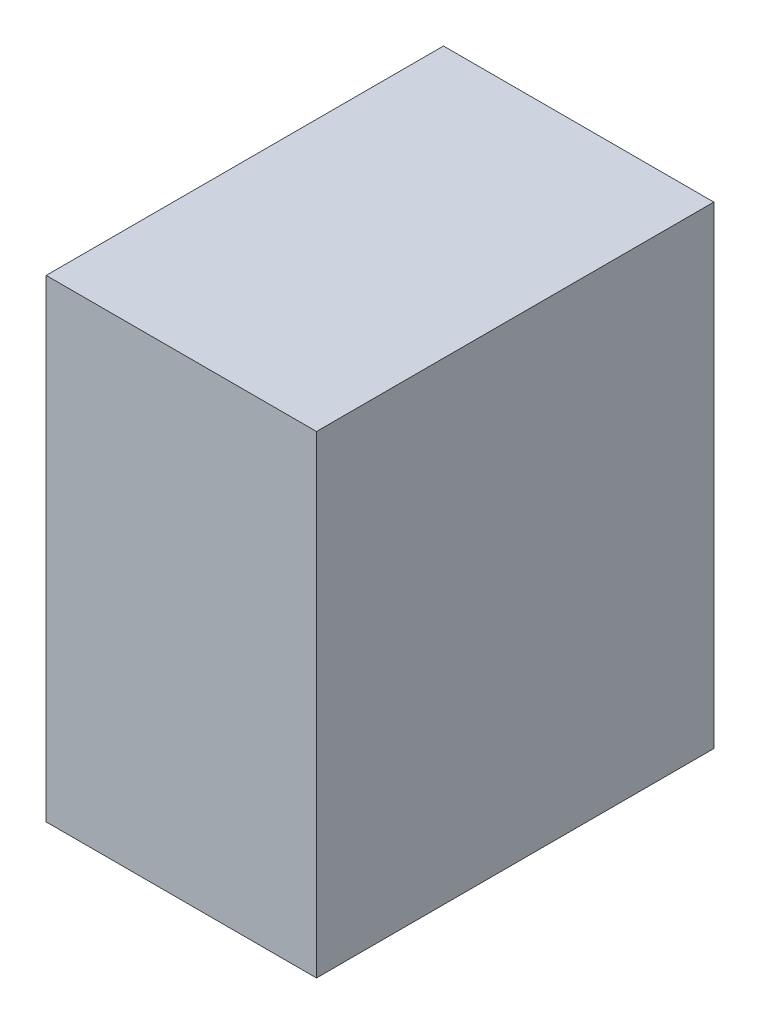
SolidWorks part; units mm, degrees
ref_plane "Front Plane" through (0, 0, 0) normal (0, 0, 1) x (1, 0, 0)
ref_plane "Top Plane" through (0, 0, 0) normal (0, 1, 0) x (1, 0, 0)
ref_plane "Right Plane" through (0, 0, 0) normal (1, 0, 0) x (0, 0, -1)
sketch "Sketch1" plane through (-13.7935, 0, 0) normal (1, 0, 0) x (0, 0, -1)
  line L0 (-27.3734, -29.2899) -> (-27.3734, -28.9399) construction
  line L1 (-27.3734, -29.1968) -> (-27.2338, -29.1968)
  line L2 (-27.3734, -29.1968) -> (-27.3734, -29.0304)
  line L3 (-27.3734, -29.0304) -> (-27.2338, -29.0304)
  line L4 (-27.2338, -29.1968) -> (-27.2338, -29.0304)
  point P6 (-27.2338, -29.1968)
extrude "Boss-Extrude1" add sketch "Sketch1" along normal blind 0.095
